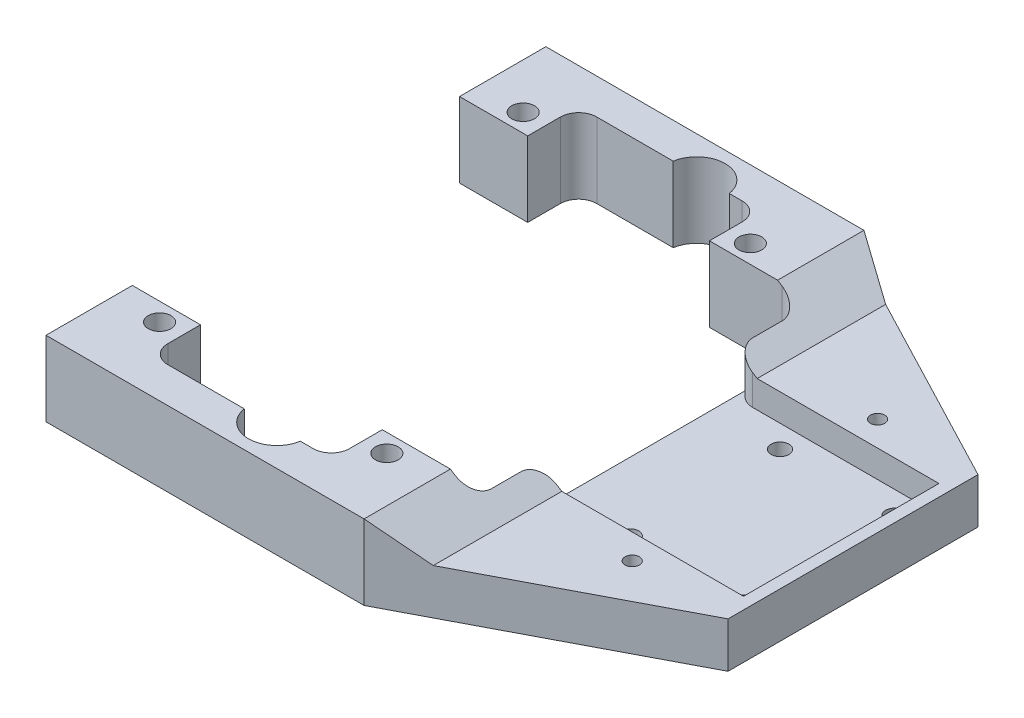
SolidWorks part; units mm, degrees
ref_plane "Front Plane" through (0, 0, 0) normal (0, 0, 1) x (1, 0, 0)
ref_plane "Top Plane" through (0, 0, 0) normal (0, 1, 0) x (1, 0, 0)
ref_plane "Right Plane" through (0, 0, 0) normal (1, 0, 0) x (0, 0, -1)
sketch "Sketch1" plane through (0, 0, 0) normal (0, 1, 0) x (1, 0, 0)
  line L0 (55.625, 17.4625) -> (22.225, 34.925)
  line L1 (-15.875, -25.4) -> (15.875, -25.4) construction
  line L2 (-15.875, -25.4) -> (-15.875, 25.4) construction
  line L3 (-15.875, 25.4) -> (15.875, 25.4) construction
  line L4 (15.875, -25.4) -> (15.875, 25.4) construction
  line L5 (-15.875, -25.4) -> (15.875, 25.4) construction
  line L6 (-15.875, 25.4) -> (15.875, -25.4) construction
  line L7 (22.225, -34.925) -> (-22.225, -34.925)
  line L8 (22.225, -34.925) -> (22.225, 34.925) construction
  line L9 (22.225, 34.925) -> (-22.225, 34.925)
  line L10 (-22.225, -34.925) -> (-22.225, 34.925)
  line L11 (22.225, -34.925) -> (-22.225, 34.925) construction
  line L12 (22.225, 34.925) -> (-22.225, -34.925) construction
  line L13 (34.925, -10.5) -> (50.925, -10.5) construction
  line L14 (34.925, -10.5) -> (34.925, 10.5) construction
  line L15 (34.925, 10.5) -> (50.925, 10.5) construction
  line L16 (50.925, -10.5) -> (50.925, 10.5) construction
  line L17 (34.925, -10.5) -> (50.925, 10.5) construction
  line L18 (34.925, 10.5) -> (50.925, -10.5) construction
  line L19 (30.225, 17.4625) -> (55.625, 17.4625) construction
  line L20 (30.225, 17.4625) -> (30.225, -17.4625) construction
  line L21 (30.225, -17.4625) -> (55.625, -17.4625) construction
  line L22 (55.625, 17.4625) -> (55.625, -17.4625)
  line L23 (30.225, 17.4625) -> (55.625, -17.4625) construction
  line L24 (30.225, -17.4625) -> (55.625, 17.4625) construction
  line L25 (55.625, -17.4625) -> (22.225, -34.925)
  circle A0 centre (-15.875, 25.4) radius 1.5875
  circle A1 centre (15.875, 25.4) radius 1.5875
  circle A2 centre (15.875, -25.4) radius 1.5875
  circle A3 centre (-15.875, -25.4) radius 1.5875
  circle A4 centre (50.925, 10.5) radius 1.25
  circle A5 centre (50.925, -10.5) radius 1.25
  circle A6 centre (34.925, -10.5) radius 1.25
  circle A8 centre (34.925, 10.5) radius 1.25
  point P0 (0, 0)
  point P7 (0, 0)
  point P15 (42.925, 0)
  point P23 (42.925, 0)
  dimension "D3" = 3.175
  dimension "D8" = 2.5
  dimension "D1" = 50.8
  dimension "D2" = 31.75
  dimension "D4" = 69.85
  dimension "D5" = 6.35
  dimension "D6" = 21
  dimension "D7" = 16
  dimension "D9" = 25.4
  dimension "D10" = 34.925
  dimension "D11" = 12.7
extrude "Boss-Extrude1" add sketch "Sketch1" along normal blind 2.54
sketch "Sketch2" plane through (0, 2.54, 0) normal (0, 1, 0) x (1, 0, 0)
  line L5 (22.225, 17.582) -> (25.4, 17.582)
  line L6 (22.225, 17.582) -> (0.2018, 17.582)
  line L7 (22.225, 17.582) -> (22.225, -17.582) construction
  line L8 (22.225, 17.582) -> (22.225, -17.582) construction
  line L9 (22.225, -17.582) -> (0.2018, -17.582)
  line L10 (0.2018, 17.582) -> (0.2018, -17.582)
  line L11 (22.225, 17.582) -> (0.2018, -17.582) construction
  line L12 (22.225, -17.582) -> (0.2018, 17.582) construction
  line L13 (22.225, -17.582) -> (25.4, -17.582)
  line L14 (25.4, 17.582) -> (25.4, -17.582)
  point P0 (0, 0)
  point P1 (11.2134, 0)
  dimension "D1" = 3.175
extrude "Cut-Extrude1" cut sketch "Sketch2" against normal blind 2.54
sketch "Sketch3" plane through (0, 2.54, 0) normal (0, 1, 0) x (1, 0, 0)
  line L5 (28.575, 31.605) -> (28.575, 13.6525)
  line L9 (0, 0) -> (25.4, 0) construction
  line L10 (25.4, -17.582) -> (25.4, 17.582) construction
  line L21 (28.575, -13.6525) -> (53.975, -13.6525) construction
  line L29 (55.625, 17.4625) -> (22.225, 34.925) construction
  line L32 (22.225, -34.925) -> (55.625, -17.4625) construction
  line L33 (53.975, -13.6525) -> (53.975, 13.6525)
  line L34 (28.575, -13.6525) -> (28.575, 13.6525) construction
  line L35 (28.575, 13.6525) -> (53.975, 13.6525) construction
  line L36 (53.975, -13.6525) -> (53.975, 13.6525) construction
  line L37 (28.575, -13.6525) -> (53.975, 13.6525) construction
  line L38 (28.575, 13.6525) -> (53.975, -13.6525) construction
  line L39 (28.575, 13.6525) -> (53.975, 13.6525)
  line L42 (28.575, -13.6525) -> (28.575, -31.605)
  line L44 (28.575, -13.6525) -> (53.975, -13.6525)
  line L46 (28.575, 31.605) -> (55.625, 17.4625)
  line L47 (28.575, -31.605) -> (55.625, -17.4625)
  line L48 (55.625, -17.4625) -> (55.625, 17.4625)
  point P5 (41.275, 0)
  dimension "D1" = 3.175
  dimension "D2" = 27.305
  dimension "1" = 25.4
extrude "Boss-Extrude2" add sketch "Sketch3" along normal blind 3.81
sketch "Sketch5" plane through (0, 2.54, 0) normal (0, 1, 0) x (1, 0, 0)
  line L0 (25.4, 17.582) -> (0.2018, 17.582) construction
  line L1 (-22.225, 34.925) -> (22.225, 34.925)
  line L2 (-22.225, 34.925) -> (-22.225, 17.582)
  line L3 (-22.225, 17.582) -> (22.225, 17.582)
  line L4 (22.225, 34.925) -> (22.225, 17.582)
  line L5 (-22.225, 34.925) -> (-22.225, -34.925) construction
  line L6 (22.225, -34.925) -> (-22.225, -34.925)
  line L8 (22.225, -17.582) -> (-22.225, -17.582)
  line L9 (-22.225, -34.925) -> (-22.225, -17.582)
  line L12 (22.225, -34.925) -> (22.225, -17.582)
  circle A0 centre (15.875, -25.4) radius 1.5875
  circle A1 centre (-15.875, -25.4) radius 1.5875
  circle A2 centre (-15.875, 25.4) radius 1.5875
  circle A3 centre (15.875, 25.4) radius 1.5875
extrude "Boss-Extrude3" add sketch "Sketch5" along normal blind 7.9375
sketch "Sketch6" plane through (0, 2.54, 0) normal (0, 1, 0) x (1, 0, 0)
  line L1 (-12.6537, 25.5195) -> (12.2437, 25.5195) construction
  line L4 (-22.225, 17.582) -> (0.2018, 17.582) construction
  text T0 "GPS Mount 6" font "Comic Sans MS" height 3.175
  dimension "D1" = 7.9375
sketch "Sketch7" plane through (0, 0, -34.925) normal (0, 0, -1) x (-1, 0, 0)
  line L0 (-22.225, 10.4775) -> (-28.575, 6.35)
  line L1 (-28.575, 6.35) -> (-28.575, 2.54)
  line L2 (-28.575, 2.54) -> (-22.225, 2.54)
  line L3 (-22.225, 2.54) -> (-22.225, 10.4775)
extrude "Boss-Extrude4" add sketch "Sketch7" against normal up to surface (48.5775 mm away)
sketch "Sketch8" plane through (0, 10.4775, 0) normal (0, 1, 0) x (1, 0, 0)
  line L0 (28.575, 31.605) -> (22.225, 34.925)
  line L1 (22.225, 34.925) -> (28.575, 34.925)
  line L2 (28.575, 34.925) -> (28.575, 31.605)
  line L12 (22.225, 17.582) -> (22.225, 13.6525)
  line L13 (22.225, 13.6525) -> (25.4, 13.6525)
  line L14 (28.575, 13.6525) -> (22.225, 13.6525) construction
  line L15 (25.4, 13.6525) -> (25.4, 17.582)
  line L16 (25.4, 17.582) -> (22.225, 17.582)
extrude "Cut-Extrude3" cut sketch "Sketch8" against normal up to surface (10.4775 mm away) up to face at (12.8009, 0, 0)
mirror "Mirror4" about plane through (0, 0, 0) normal (0, 0, 1) of "Cut-Extrude3", "Boss-Extrude4"
sketch "Sketch9" plane through (0, 6.35, 0) normal (0, 1, 0) x (1, 0, 0)
  line L1 (28.575, 13.6525) -> (22.225, 13.6525)
  line L2 (28.575, 13.6525) -> (28.575, -13.6525)
  line L3 (28.575, -13.6525) -> (22.225, -13.6525)
  line L4 (22.225, 13.6525) -> (22.225, -13.6525)
extrude "Cut-Extrude4" cut sketch "Sketch9" against normal up to surface (3.81 mm away) and the other way blind 9.906 up to face at (23.8125, 2.54, 0)
sketch "Sketch11" plane through (0, 10.4775, 0) normal (0, 1, 0) x (1, 0, 0)
  line L0 (-22.225, 34.925) -> (-22.225, 17.582) construction
  line L1 (25.4, -22.86) -> (-22.225, -22.86)
  line L2 (25.4, -22.86) -> (25.4, 22.86)
  line L3 (25.4, 22.86) -> (-22.225, 22.86)
  line L4 (-22.225, -22.86) -> (-22.225, 22.86)
  line L5 (25.4, -22.86) -> (-22.225, 22.86) construction
  line L6 (25.4, 22.86) -> (-22.225, -22.86) construction
  line L7 (25.4, -13.6525) -> (25.4, 13.6525) construction
  point P0 (1.5875, 0)
  dimension "D1" = 45.72
extrude "Cut-Extrude5" cut sketch "Sketch11" against normal blind 40.386
fillet "Fillet1" radius 2.54 2 edges at (25.4, 4.2069, 22.86) (25.4, 4.2069, -22.86)
sketch "Sketch12" plane through (0, 10.4775, 0) normal (0, 1, 0) x (1, 0, 0)
  line L0 (22.225, 22.86) -> (-22.225, 22.86) construction
  line L1 (-12.7, 22.86) -> (12.7, 22.86)
  line L2 (-12.7, 22.86) -> (-12.7, 29.972)
  line L3 (-12.7, 29.972) -> (12.7, 29.972)
  line L4 (12.7, 22.86) -> (12.7, 29.972)
  line L5 (0, 0) -> (3.5247, 0) construction
  line L6 (-12.7, -29.972) -> (12.7, -29.972)
  line L7 (12.7, -22.86) -> (12.7, -29.972)
  line L8 (-12.7, -22.86) -> (12.7, -22.86)
  line L9 (-12.7, -22.86) -> (-12.7, -29.972)
  circle A0 centre (-15.875, 25.4) radius 1.5875 construction
  circle A1 centre (15.875, 25.4) radius 1.5875 construction
  dimension "D1" = 3.175
  dimension "D2" = 3.175
  dimension "D3" = 7.112
extrude "Cut-Extrude6" cut sketch "Sketch12" against normal blind 22.606
fillet "Fillet2" radius 2.54 4 edges at (12.7, 5.2387, 29.972) (12.7, 5.2387, -29.972) (-12.7, 5.2387, 29.972) (-12.7, 5.2387, -29.972)
fillet "Fillet4" radius 2.54 2 edges at (25.4, 5.4769, 13.6525) (25.4, 5.4769, -13.6525)
sketch "Sketch13" plane through (0, 10.4775, 0) normal (0, 1, 0) x (1, 0, 0)
  circle A0 centre (4.445, -29.337) radius 3.9688
  circle A1 centre (4.445, 29.337) radius 3.9688
  dimension "D1" = 7.9375
  dimension "D2" = 7.9375
extrude "Cut-Extrude7" cut sketch "Sketch13" against normal blind 27.94
sketch "Sketch14" plane through (0, 0, 0) normal (0, -1, 0) x (1, 0, 0)
  line L0 (25.4, 20.32) -> (25.4, -20.32) construction
  circle A0 centre (41.91, 0) radius 17.145 construction
  circle A1 centre (41.91, 17.145) radius 1
  circle A2 centre (41.91, -17.145) radius 1
  dimension "D2" = 34.29
  dimension "D3" = 2
  dimension "D4" = 2
  dimension "D1" = 16.51
extrude "Cut-Extrude8" cut sketch "Sketch14" against normal blind 18.288
